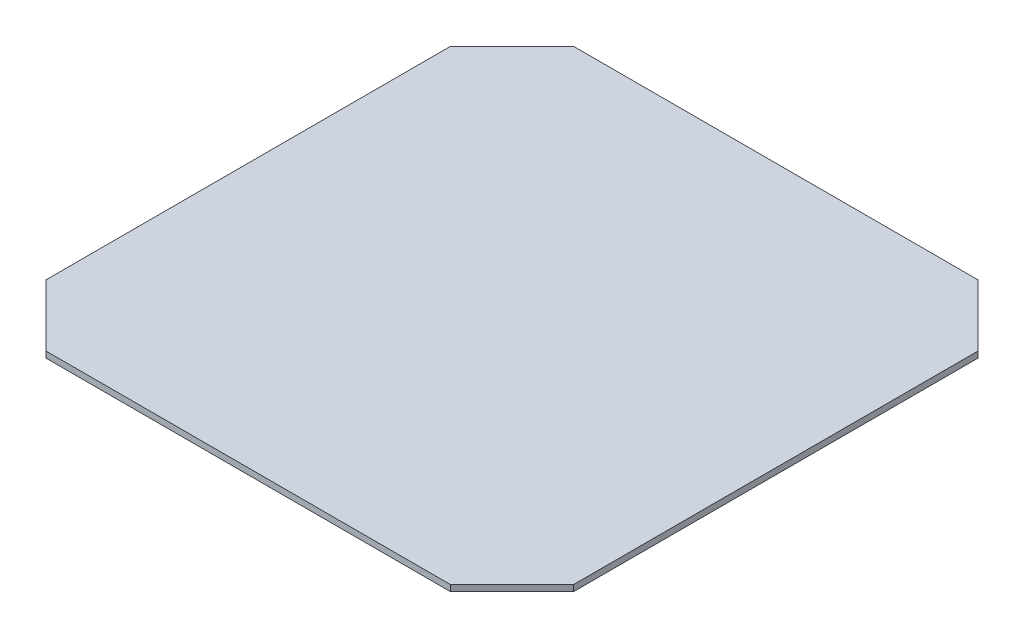
SolidWorks part; units mm, degrees
material "Vidro"
ref_plane "Plano frontal" through (0, 0, 0) normal (0, 0, 1) x (1, 0, 0)
ref_plane "Plano superior" through (0, 0, 0) normal (0, 1, 0) x (1, 0, 0)
ref_plane "Plano direito" through (0, 0, 0) normal (1, 0, 0) x (0, 0, -1)
sketch "Esboço1" plane through (0, 0, 0) normal (0, 1, 0) x (1, 0, 0)
  line L0 (0, 0) -> (0, 107) construction
  line L1 (-107, 107) -> (107, 107)
  line L2 (-107, 107) -> (-107, -107)
  line L3 (-107, -107) -> (107, -107)
  line L4 (107, 107) -> (107, -107)
  line L5 (-107, 107) -> (107, -107) construction
  line L6 (-107, -107) -> (107, 107) construction
  line L7 (0, 0) -> (107, 0) construction
  circle A0 centre (100, 100) radius 2.5
  circle A1 centre (-100, 100) radius 2.5
  circle A2 centre (100, -100) radius 2.5
  circle A3 centre (-100, -100) radius 2.5
  point P0 (0, 0)
  dimension "D2" = 5
  dimension "D3" = 200
  dimension "D1" = 214
extrude "Ressalto-extrusão1" add sketch "Esboço1" along normal mid plane 2.5
chamfer "Chanfro1" distance 25 angle 45 4 edges at (-107, 0, 107) (107, 0, 107) (107, 0, -107) (-107, 0, -107)
